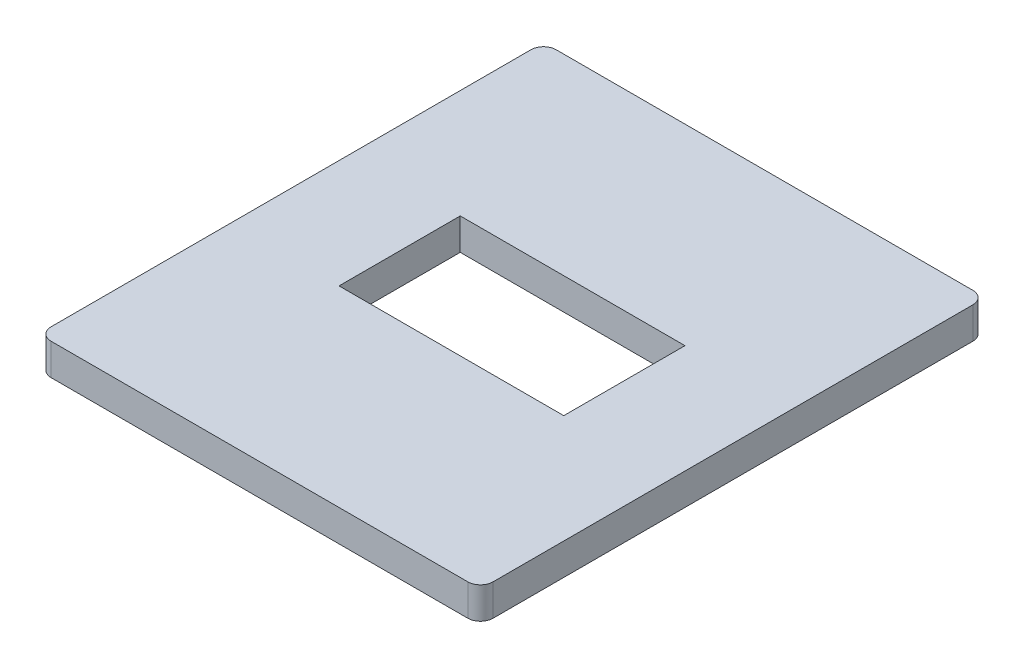
SolidWorks part; units mm, degrees
material "1060 Alloy"
ref_plane "Front Plane" through (0, 0, 0) normal (0, 0, 1) x (1, 0, 0)
ref_plane "Top Plane" through (0, 0, 0) normal (0, 1, 0) x (1, 0, 0)
ref_plane "Right Plane" through (0, 0, 0) normal (1, 0, 0) x (0, 0, -1)
sketch "Sketch1" plane through (0, 0, 0) normal (0, 1, 0) x (1, 0, 0)
  line L0 (21.8951, -23.8438) -> (21.8951, 26.9562)
  line L1 (21.8951, 26.9562) -> (-22.5549, 26.9562)
  line L2 (-22.5549, 26.9562) -> (-22.5549, -23.8438)
  line L3 (-22.5549, -23.8438) -> (21.8951, -23.8438)
  line L5 (-11.6329, -4.5398) -> (10.9731, -4.5398)
  line L6 (-11.6329, -4.5398) -> (-11.6329, 7.6522)
  line L7 (-11.6329, 7.6522) -> (10.9731, 7.6522)
  line L8 (10.9731, -4.5398) -> (10.9731, 7.6522)
  line L9 (-11.6329, -4.5398) -> (10.9731, 7.6522) construction
  line L10 (-11.6329, 7.6522) -> (10.9731, -4.5398) construction
  point P0 (10.9731, 1.5562)
  point P1 (21.8951, 1.5562)
  point P2 (-0.3299, -4.5398)
  point P3 (-0.3299, -23.8438)
  point P14 (-0.3299, 7.6522)
  point P15 (-0.3299, 26.9562)
  dimension "D1" = 22.606
  dimension "D2" = 12.192
  dimension "D3" = 50.8
  dimension "D4" = 44.45
extrude "Boss-Extrude1" add sketch "Sketch1" along normal blind 3.175
sketch "Sketch2" plane through (0, 0, -26.9562) normal (0, 0, -1) x (-1, 0, 0)
  line L0 (0.3299, 0) -> (0.3299, 3.175)
  line L1 (-21.8951, 0) -> (22.5549, 0) construction
  line L2 (-21.8951, 3.175) -> (22.5549, 3.175) construction
fillet "Fillet1" radius 1.27 4 edges at (21.8951, 1.5875, 23.8438) (21.8951, 1.5875, -26.9562) (-22.5549, 1.5875, 23.8438) (-22.5549, 1.5875, -26.9562)
sketch "Sketch3" plane through (0, 0, 23.8438) normal (0, 0, 1) x (1, 0, 0)
  line L0 (-0.3299, 3.175) -> (-0.3299, 0)
  line L1 (-21.2849, 3.175) -> (20.6251, 3.175) construction
  line L2 (-21.2849, 0) -> (20.6251, 0) construction
sketch "Sketch4" plane through (0, 3.175, 0) normal (0, 1, 0) x (1, 0, 0)
  line L0 (-22.5549, 1.5562) -> (21.8951, 1.5562)
  line L1 (-22.5549, 25.6862) -> (-22.5549, -22.5738) construction
  line L2 (21.8951, -22.5738) -> (21.8951, 25.6862) construction
  line L3 (-0.3299, 26.9562) -> (-0.3299, -23.8438)
  line L4 (20.6251, 26.9562) -> (-21.2849, 26.9562) construction
  line L5 (-21.2849, -23.8438) -> (20.6251, -23.8438) construction
